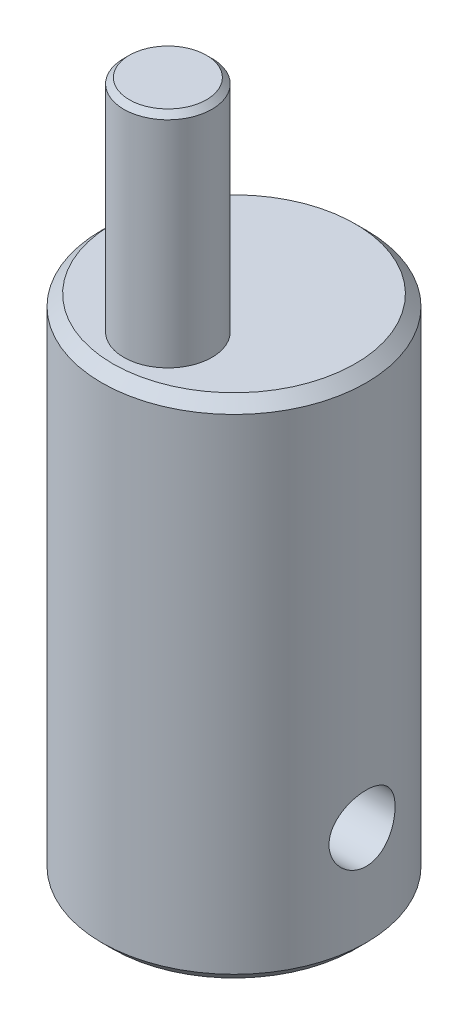
SolidWorks part; units mm, degrees
ref_plane "Front Plane" through (0, 0, 0) normal (0, 0, 1) x (1, 0, 0)
ref_plane "Top Plane" through (0, 0, 0) normal (0, 1, 0) x (1, 0, 0)
ref_plane "Right Plane" through (0, 0, 0) normal (1, 0, 0) x (0, 0, -1)
sketch "Sketch1" plane through (0, 0, 0) normal (0, 1, 0) x (1, 0, 0)
  circle A0 centre (0, 0) radius 6
  dimension "D1" = 12
extrude "Boss-Extrude1" add sketch "Sketch1" along normal blind 23
sketch "Sketch2" plane through (0, 23, 0) normal (0, 1, 0) x (1, 0, 0)
  circle A1 centre (0, -3) radius 2
  dimension "D1" = 4
  dimension "D2" = 3
extrude "Boss-Extrude2" add sketch "Sketch2" along normal blind 10
sketch "Sketch3" plane through (0, 0, 0) normal (1, 0, 0) x (0, 0, -1)
  circle A0 centre (0, 5) radius 1.5
  point P2 (0, 0)
  dimension "D1" = 3
  dimension "D2" = 5
extrude "Cut-Extrude1" cut sketch "Sketch3" against normal through all and the other way through all
chamfer "Chamfer1" distance 0.25 angle 45 1 edges at (0, 33, 5)
chamfer "Chamfer2" distance 0.5 angle 45 2 edges at (0, 0, 6) (0, 23, 6)
